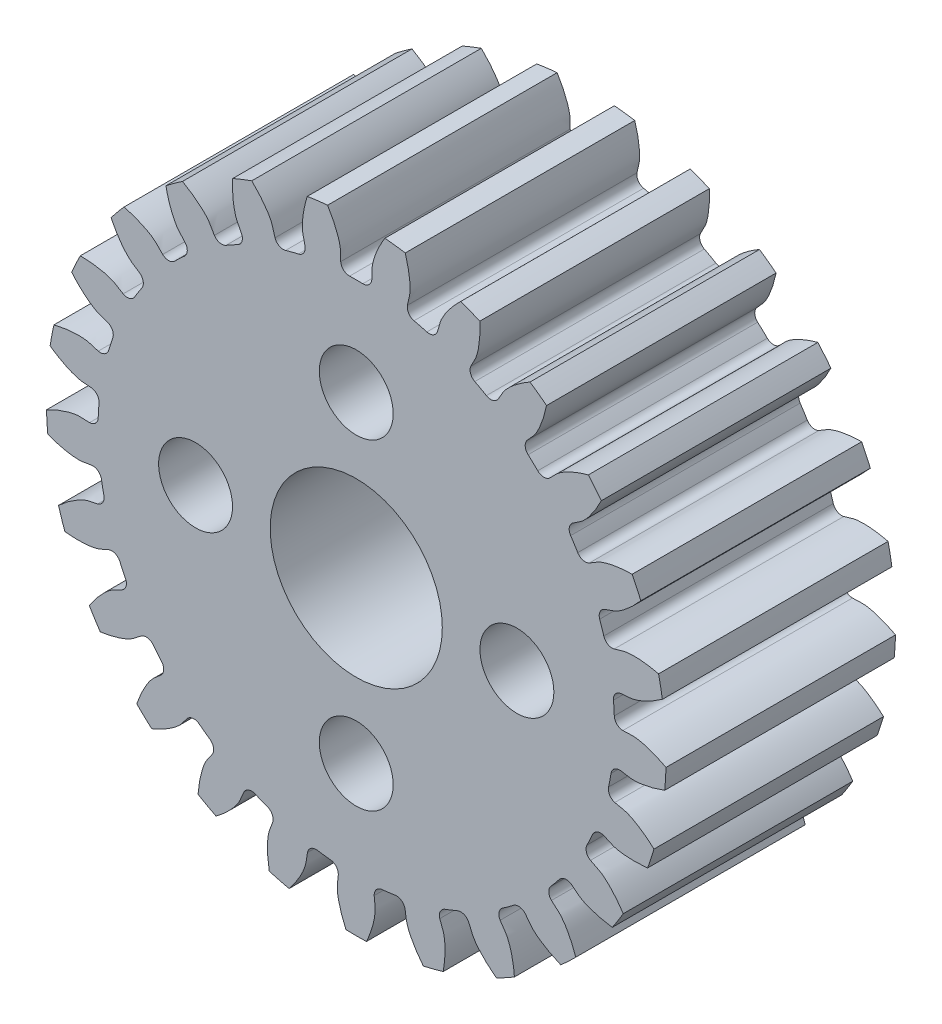
SolidWorks part; units mm, degrees
ref_plane "前视基准面" through (0, 0, 0) normal (0, 0, 1) x (1, 0, 0)
ref_plane "上视基准面" through (0, 0, 0) normal (0, 1, 0) x (1, 0, 0)
ref_plane "右视基准面" through (0, 0, 0) normal (1, 0, 0) x (0, 0, -1)
other "Configuration Table"
ref_axis "Axis1" through (0, 0, -88.99) along (0, 0, 1)
sketch "草图1" plane through (0, 0, 0) normal (0, 0, 1) x (1, 0, 0)
  circle A0 centre (0, 0) radius 13.5
extrude "LaShenA" add sketch "草图1" along normal blind 10
sketch "SketchA" plane through (0, 0, 10) normal (0, 0, 1) x (1, 0, 0)
  line L0 (0, 0) -> (0, 13.5) construction
  arc A0 (0.2884, 11.2463) -> (-0.2884, 11.2463) centre (0, 0) ccw
  arc A1 (1.6373, 14.0052) -> (-1.6373, 14.0052) centre (0, 0) ccw
  arc A2 (-0.2884, 11.2463) -> (-0.6771, 11.5977) centre (-0.2981, 11.6262) cw
  arc A3 (0.6771, 11.5977) -> (0.2884, 11.2463) centre (0.2981, 11.6262) cw
  circle A4 centre (0, 0) radius 12.1018 construction
  circle A5 centre (0, 0) radius 13.5 construction
  circle A6 centre (0, 0) radius 11.25 construction
  circle A7 centre (0, 0) radius 12.5 construction
  spline S0 degree 3 poles (0.6771, 11.5977) (0.6892, 11.759) (0.675, 11.9481) (0.7011, 12.1466) (0.7108, 12.198) (0.7194, 12.2387) (0.7304, 12.2854) (0.744, 12.3381) (0.7606, 12.3966) (0.7804, 12.4609) (0.8038, 12.5307) (0.8308, 12.606) (0.862, 12.6866) (0.8974, 12.7725) (0.9373, 12.8633) (0.982, 12.959) (1.0318, 13.0594) (1.0868, 13.1643) (1.1473, 13.2735) (1.2136, 13.3868) (1.2858, 13.504) (1.3641, 13.6249) (1.4795, 13.7942) (1.5723, 13.9206) (1.6373, 14.0052) knots 0.123706 0.123706 0.123706 0.123706 0.284027 0.310496 0.322147 0.335916 0.351803 0.369808 0.389932 0.412174 0.436535 0.463013 0.49161 0.522325 0.555159 0.590111 0.627181 0.666369 0.707676 0.751101 0.796644 0.844306 0.894085 1 1 1 1
  spline S1 degree 3 poles (-0.6771, 11.5977) (-0.6892, 11.759) (-0.675, 11.9481) (-0.7011, 12.1466) (-0.7108, 12.198) (-0.7194, 12.2387) (-0.7304, 12.2854) (-0.744, 12.3381) (-0.7606, 12.3966) (-0.7804, 12.4609) (-0.8038, 12.5307) (-0.8308, 12.606) (-0.862, 12.6866) (-0.8974, 12.7725) (-0.9373, 12.8633) (-0.982, 12.959) (-1.0318, 13.0594) (-1.0868, 13.1643) (-1.1473, 13.2735) (-1.2136, 13.3868) (-1.2858, 13.504) (-1.3641, 13.6249) (-1.4795, 13.7942) (-1.5723, 13.9206) (-1.6373, 14.0052) knots 0.123706 0.123706 0.123706 0.123706 0.284027 0.310496 0.322147 0.335916 0.351803 0.369808 0.389932 0.412174 0.436535 0.463013 0.49161 0.522325 0.555159 0.590111 0.627181 0.666369 0.707676 0.751101 0.796644 0.844306 0.894085 1 1 1 1
  dimension "D1" = 0.38
  dimension "Db" = 24.2037
  dimension "Da" = 27
  dimension "Df" = 22.5
  dimension "Dn" = 25
extrude "Cut-ExtrudeA" cut sketch "SketchA" against normal blind 10
pattern_circular "www.KYTool.cn" count 25 over 360 about axis through (0, 0, -88.99) along (0, 0, 1) of "Cut-ExtrudeA"
sketch "草图3" plane through (0, 0, 10) normal (0, 0, 1) x (1, 0, 0)
  circle A0 centre (0, 0) radius 10.1
  dimension "D1" = 20.2
sketch "草图4" plane through (0, 0, 10) normal (0, 0, 1) x (1, 0, 0)
  circle A0 centre (0, 0) radius 7 construction
  circle A1 centre (0, 7) radius 1.61
  circle A2 centre (7, 0) radius 1.61
  circle A3 centre (0, -7) radius 1.61
  circle A4 centre (-7, 0) radius 1.61
  circle A5 centre (0, 0) radius 3.75
  point P14 (0, 0)
  dimension "D1" = 14
  dimension "D2" = 3.22
  dimension "D4" = 7.5
  dimension "D3" = 4
extrude "切除-拉伸2" cut sketch "草图4" against normal blind 10
